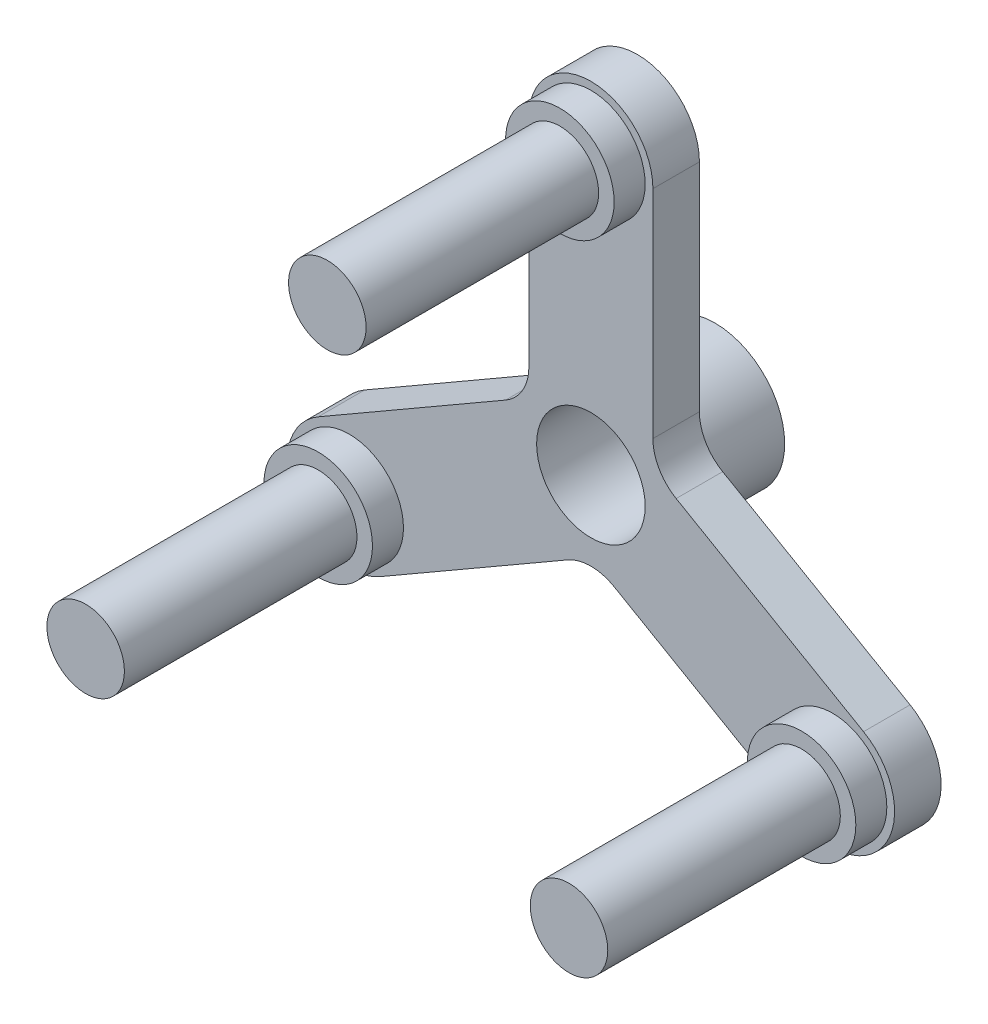
SolidWorks part; units mm, degrees
ref_plane "Front Plane" through (0, 0, 0) normal (0, 0, 1) x (1, 0, 0)
ref_plane "Top Plane" through (0, 0, 0) normal (0, 1, 0) x (1, 0, 0)
ref_plane "Right Plane" through (0, 0, 0) normal (1, 0, 0) x (0, 0, -1)
sketch "Sketch2" plane through (0, 0, 0) normal (0, 0, 1) x (1, 0, 0)
  line L0 (0, 0) -> (0, 18) construction
  line L1 (-4, 0) -> (-4, 18)
  line L2 (4, 0) -> (4, 18)
  arc A0 (-4, 0) -> (4, 0) centre (0, 0) ccw
  arc A1 (4, 18) -> (-4, 18) centre (0, 18) ccw
  circle A3 centre (0, 0) radius 3.5
  point P3 (0, 9)
  dimension "D3" = 7
  dimension "D1" = 8
  dimension "D2" = 18
extrude "Boss-Extrude1" add sketch "Sketch2" along normal blind 3
sketch "Sketch3" plane through (0, 0, 3) normal (0, 0, 1) x (1, 0, 0)
  circle A0 centre (0, 18) radius 3.5
  dimension "D1" = 7
extrude "Boss-Extrude2" add sketch "Sketch3" along normal blind 2
sketch "Sketch4" plane through (0, 0, 5) normal (0, 0, 1) x (1, 0, 0)
  circle A0 centre (0, 18) radius 2.5
  dimension "D1" = 5
extrude "Boss-Extrude3" add sketch "Sketch4" along normal blind 15
pattern_circular "CirPattern1" count 3 over 360 about axis through (0, 0, 0) along (0, 0, 1) of "Boss-Extrude3", "Boss-Extrude2", "Boss-Extrude1"
fillet "Fillet1" radius 3 3 edges at (4, 2.3094, 1.5) (0, -4.6188, 1.5) (-4, 2.3094, 1.5)
sketch "Sketch5" plane through (0, 0, 0) normal (0, 0, -1) x (-1, 0, 0)
  circle A1 centre (0, 0) radius 3.5
  circle A2 centre (0, 0) radius 4.5
  dimension "D1" = 9
  dimension "D2" = 7
extrude "Boss-Extrude4" add sketch "Sketch5" along normal blind 5
